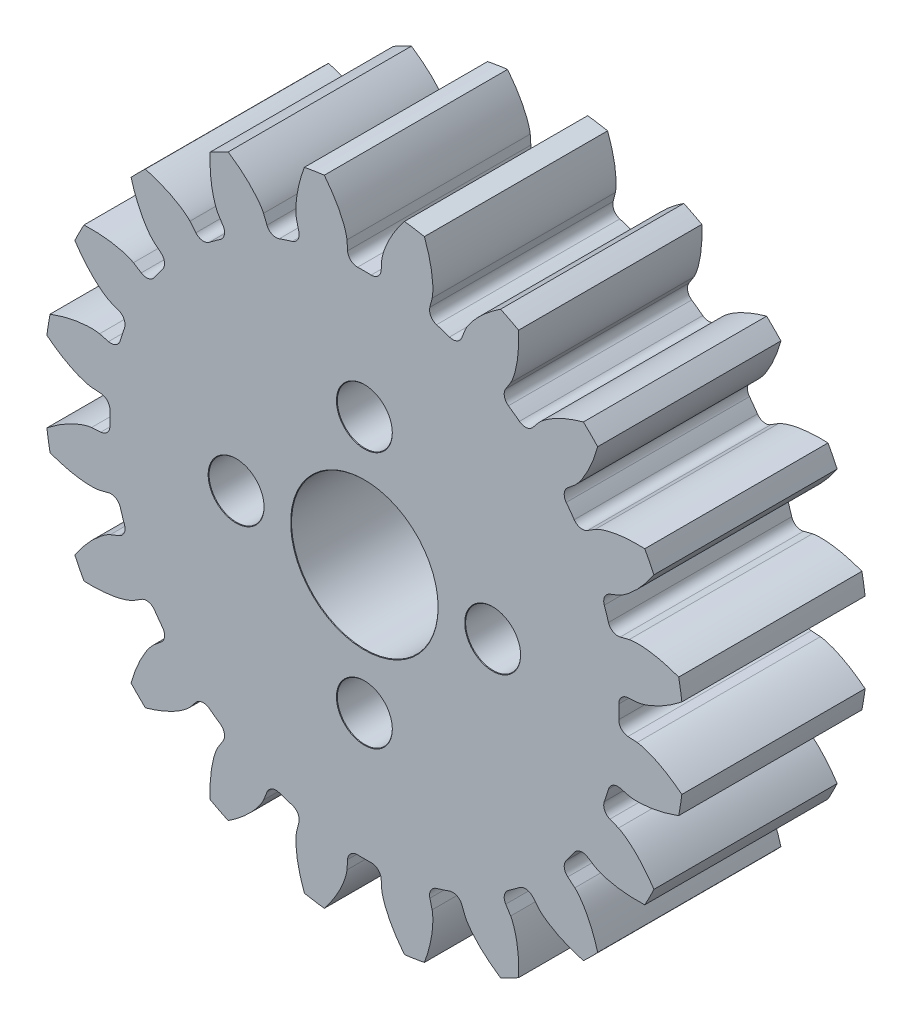
SolidWorks part; units mm, degrees
ref_plane "Front Plane" through (0, 0, 0) normal (0, 0, 1) x (1, 0, 0)
ref_plane "Top Plane" through (0, 0, 0) normal (0, 1, 0) x (1, 0, 0)
ref_plane "Right Plane" through (0, 0, 0) normal (1, 0, 0) x (0, 0, -1)
sketch "Sketch1" plane through (0, 0, 0) normal (0, 0, 1) x (1, 0, 0)
  line L0 (0, 0) -> (0, 15.875) construction
  line L1 (-5.1021, 17.732) -> (5.1021, 14.018) construction
  circle A0 centre (0, 0) radius 13.8906 construction
  circle A1 centre (0, 0) radius 17.4625 construction
  circle A2 centre (0, 0) radius 15.875 construction
  circle A3 centre (0, 0) radius 14.9176 construction
  point P8 (203.2, 0)
  point P13 (254, 0)
  dimension "OD | Outside Diameter" = 34.925
  dimension "Root Diameter" = 27.7812
  dimension "Gear Pitch Diameter" = 31.75
  dimension "Base Diameter" = 29.8352
  dimension "Pressure Angle" = 20
  dimension "Number of Teeth" = 508
  dimension "Gear Pitch | Diametral Pitch" = 406.4
sketch "Sketch2" plane through (0, 0, 0) normal (1, 0, 0) x (0, 0, -1)
  line L0 (-5, 0) -> (5, 0) construction
  point P2 (12.4625, 0)
  point P5 (21.1937, 0)
  point P6 (-12.4625, 0)
  dimension "Length" = 10
  dimension "D1" = 17.4625
  dimension "D2" = 26.1937
  dimension "D3" = 17.4625
sketch "Sketch3" plane through (0, 0, 0) normal (0, 0, 1) x (1, 0, 0)
  circle A0 centre (0, 0) radius 17.4625
  circle A1 centre (0, 0) radius 17.4625 construction
extrude "Boss-Extrude1" add sketch "Sketch3" against normal up to vertex (5 mm away) and the other way up to vertex (5 mm away) up to point (0, 0, -5) other way up to point (0, 0, 5)
sketch "Sketch4" plane through (0, 0, 0) normal (0, 0, 1) x (1, 0, 0)
  line L0 (0, 0) -> (13.8625, 0.8833) construction
  line L2 (0, 0) -> (13.8625, -0.8833) construction
  line L4 (13.8625, 0.8833) -> (14.8874, 0.9486)
  line L5 (14.8874, -0.9486) -> (13.8625, -0.8833)
  arc A0 (13.8625, 0.8833) -> (13.8625, -0.8833) centre (0, 0) cw
  arc A3 (17.3252, 2.1857) -> (17.3252, -2.1857) centre (0, 0) cw
  circle A4 centre (0, 0) radius 17.4625 construction
  spline S0 degree 4 poles (14.8874, 0.9486) (14.8915, 0.949) (14.9029, 0.95) (14.9244, 0.9526) (14.9595, 0.9578) (15.0039, 0.9657) (15.0613, 0.9774) (15.1285, 0.9932) (15.2021, 1.0126) (15.2819, 1.036) (15.3611, 1.0612) (15.4397, 1.0882) (15.5178, 1.1167) (15.612, 1.1532) (15.7243, 1.1996) (15.8547, 1.2576) (16.0015, 1.3281) (16.1499, 1.4047) (16.2948, 1.484) (16.44, 1.5687) (16.5795, 1.6539) (16.7229, 1.7469) (16.8547, 1.8351) (17.0006, 1.939) (17.1179, 2.0243) (17.2707, 2.1422) (17.3604, 2.2134) (17.4647, 2.2985) (17.5107, 2.3373) (17.539, 2.3612) knots 0 0 0 0 0 0.005377 0.015084 0.028532 0.04661 0.064855 0.092111 0.119476 0.146842 0.174209 0.201575 0.228941 0.256307 0.307035 0.361767 0.4165 0.471232 0.525964 0.580697 0.635429 0.690161 0.744894 0.799626 0.854358 0.909091 0.954545 1 1 1 1 1 construction
  spline S1 degree 4 poles (14.8874, 0.9486) (14.8915, 0.949) (14.9029, 0.95) (14.9244, 0.9526) (14.9595, 0.9578) (15.0039, 0.9657) (15.0613, 0.9774) (15.1285, 0.9932) (15.2021, 1.0126) (15.2819, 1.036) (15.3611, 1.0612) (15.4397, 1.0882) (15.5178, 1.1167) (15.612, 1.1532) (15.7243, 1.1996) (15.8547, 1.2576) (16.0015, 1.3281) (16.1499, 1.4047) (16.2948, 1.484) (16.44, 1.5687) (16.5795, 1.6539) (16.7229, 1.7469) (16.8547, 1.8351) (17.0006, 1.939) (17.1179, 2.0243) (17.2376, 2.1166) (17.2956, 2.1622) (17.3252, 2.1857) knots 0 0 0 0 0 0.005377 0.015084 0.028532 0.04661 0.064855 0.092111 0.119476 0.146842 0.174209 0.201575 0.228941 0.256307 0.307035 0.361767 0.4165 0.471232 0.525964 0.580697 0.635429 0.690161 0.744894 0.799626 0.854358 0.909091 0.909091 0.909091 0.909091 0.909091
  spline S2 degree 4 poles (14.8874, -0.9486) (14.8915, -0.949) (14.9029, -0.95) (14.9244, -0.9526) (14.9595, -0.9578) (15.0039, -0.9657) (15.0613, -0.9774) (15.1285, -0.9932) (15.2021, -1.0126) (15.2819, -1.036) (15.3611, -1.0612) (15.4397, -1.0882) (15.5178, -1.1167) (15.612, -1.1532) (15.7243, -1.1996) (15.8547, -1.2576) (16.0015, -1.3281) (16.1499, -1.4047) (16.2948, -1.484) (16.44, -1.5687) (16.5795, -1.6539) (16.7229, -1.7469) (16.8547, -1.8351) (17.0006, -1.939) (17.1179, -2.0243) (17.2707, -2.1422) (17.3604, -2.2134) (17.4647, -2.2985) (17.5107, -2.3373) (17.539, -2.3612) knots 0 0 0 0 0 0.005377 0.015084 0.028532 0.04661 0.064855 0.092111 0.119476 0.146842 0.174209 0.201575 0.228941 0.256307 0.307035 0.361767 0.4165 0.471232 0.525964 0.580697 0.635429 0.690161 0.744894 0.799626 0.854358 0.909091 0.954545 1 1 1 1 1 construction
  spline S3 degree 4 poles (14.8874, -0.9486) (14.8915, -0.949) (14.9029, -0.95) (14.9244, -0.9526) (14.9595, -0.9578) (15.0039, -0.9657) (15.0613, -0.9774) (15.1285, -0.9932) (15.2021, -1.0126) (15.2819, -1.036) (15.3611, -1.0612) (15.4397, -1.0882) (15.5178, -1.1167) (15.612, -1.1532) (15.7243, -1.1996) (15.8547, -1.2576) (16.0015, -1.3281) (16.1499, -1.4047) (16.2948, -1.484) (16.44, -1.5687) (16.5795, -1.6539) (16.7229, -1.7469) (16.8547, -1.8351) (17.0006, -1.939) (17.1179, -2.0243) (17.2376, -2.1166) (17.2956, -2.1622) (17.3252, -2.1857) knots 0 0 0 0 0 0.005377 0.015084 0.028532 0.04661 0.064855 0.092111 0.119476 0.146842 0.174209 0.201575 0.228941 0.256307 0.307035 0.361767 0.4165 0.471232 0.525964 0.580697 0.635429 0.690161 0.744894 0.799626 0.854358 0.909091 0.909091 0.909091 0.909091 0.909091
  dimension "D1" = 27.7812
extrude "Cut-Extrude1" cut sketch "Sketch4" against normal through all both and the other way through all
fillet "Fillet1" radius 0.5326 2 edges at (13.8625, -0.8833, 0) (13.8625, 0.8833, 0)
pattern_circular "CirPattern1" count 20 over 360 about axis through (0, 0, 5) along (0, 0, -1) of "Cut-Extrude1", "Fillet1"
sketch "Sketch6" plane through (0, 0, 5) normal (0, 0, 1) x (1, 0, 0)
  point P0 (0, 0)
hole_wizard "Ø8.0mm Dowel Hole1" positions "Sketch6" profile "Sketch7" hole size "Ø8.0" standard "ANSI Metric" end condition through all
sketch "Sketch7" plane through (0, 0, 5) normal (1, 0, 0) x (0, -1, 0)
  line L0 (0, 0) -> (0, 10)
  line L1 (0, 10) -> (4, 10)
  line L2 (4, 10) -> (4, 0.025)
  line L3 (4, 0.025) -> (4.025, 0)
  line L5 (4.025, 0) -> (0, 0)
  line L6 (-4, 0.025) -> (-4.025, 0) construction
  line L11 (0, -6.35) -> (0, 107.95) construction
  dimension "Thru Hole Dia." = 8
  dimension "Thru Hole Depth" = 10
  dimension "Near C'Sink Dia." = 8.05
  dimension "Near C'Sink Angle" = 90
sketch "Sketch8" plane through (0, 0, 5) normal (0, 0, 1) x (1, 0, 0)
  point P0 (0, 7)
  point P1 (7, 0)
  point P3 (0, -7)
  point P6 (-7, 0)
hole_wizard "Ø3.0mm Dowel Hole1" positions "Sketch8" profile "Sketch9" hole size "Ø3.0" standard "ANSI Metric" end condition through all
sketch "Sketch9" plane through (0, 7, 5) normal (1, 0, 0) x (0, -1, 0)
  line L0 (0, 0) -> (0, 10)
  line L1 (0, 10) -> (1.5, 10)
  line L2 (1.5, 10) -> (1.5, 0.025)
  line L3 (1.5, 0.025) -> (1.525, 0)
  line L5 (1.525, 0) -> (0, 0)
  line L6 (-1.5, 0.025) -> (-1.525, 0) construction
  line L11 (0, -6.35) -> (0, 107.95) construction
  dimension "Thru Hole Dia." = 3
  dimension "Thru Hole Depth" = 10
  dimension "Near C'Sink Dia." = 3.05
  dimension "Near C'Sink Angle" = 90
equation "\"Root Diameter@Sketch1\"=\"Root Diameter\""
equation "\"OD | Outside Diameter@Sketch1\"=\"Outside Diameter\""
equation "\"D1@CirPattern1\"=\"Number of Teeth\""
equation "\"Diametral Pitch\"= 16"
equation "\"Number of Teeth\"= 20"
equation "\"Pressure Angle\"=20"
equation "\"Pitch Diameter\"= \"Number of Teeth\" / \"Diametral Pitch\""
equation "\"Base Diameter\"= \"Pitch Diameter\" * cos ( \"Pressure Angle\" )"
equation "\"Outside Diameter\"= ( \"Number of Teeth\" + 2 ) / \"Diametral Pitch\""
equation "\"Dedendum\"= 1.25 / \"Diametral Pitch\""
equation "\"Root Diameter\"= \"Pitch Diameter\" - ( 2 * \"Dedendum\" )"
equation "\"Pitch Angle\"= 360deg / \"Number of Teeth\""
equation "\"Alpha\"= sqr ( \"Pitch Diameter\" ^ 2 - \"Base Diameter\" ^ 2 ) / \"Base Diameter\" * 180 / PI - \"Pressure Angle\""
equation "\"Beta\"= ( \"Pitch Angle\" / 4 - \"Alpha\" )"
equation "\"Phi\"= sqr ( ( \"Outside Diameter\" / 2 ) ^ 2 - ( \"Base Diameter\" / 2 ) ^ 2 ) / ( \"Base Diameter\" / 2 )"
equation "\"Addendum\"= 1 / \"Diametral Pitch\""
equation "\"WorkingDepth\"= 2 / \"Diametral Pitch\""
equation "\"WholeDepth\"= 2.25 / \"Diametral Pitch\""
equation "\"Clearance\"= 0.25 / \"Diametral Pitch\""
equation "\"ToothThickness\"= ( pi * 2 ) / \"Diametral Pitch\""
equation "\"CircularPitch\"= pi / \"Diametral Pitch\""
equation "\"Number of Teeth@Sketch1\"=\"Number of Teeth\""
equation "\"Gear Pitch | Diametral Pitch@Sketch1\"=\"Diametral Pitch\""
equation "\"Pressure Angle@Sketch1\"=\"Pressure Angle\""
equation "\"Gear Pitch Diameter@Sketch1\"=\"Pitch Diameter\""
equation "\"Base Diameter@Sketch1\"=\"Base Diameter\""
equation "\"Fillet\"= \"Clearance\" * cos ( \"Pressure Angle\" ) * tan ( ( 90 + \"Pressure Angle\" ) / 2 )"
equation "\"D1@Fillet1\"=\"Fillet\""
equation "\"D1@Sketch4\"=if( \"Base Diameter\">\"Root Diameter\",\"Root Diameter\",\"Base Diameter\"-.00001)"
equation "\"D1@Sketch2\"=\"OD | Outside Diameter@Sketch1\"*2*0.5*0.5"
equation "\"D2@Sketch2\"=\"D1@Sketch2\"*1.5"
equation "\"D3@Sketch2\"=\"D1@Sketch2\""
equation "\"Length\"= 1cm"
equation "\"Length@Sketch2\"= \"Length\""
